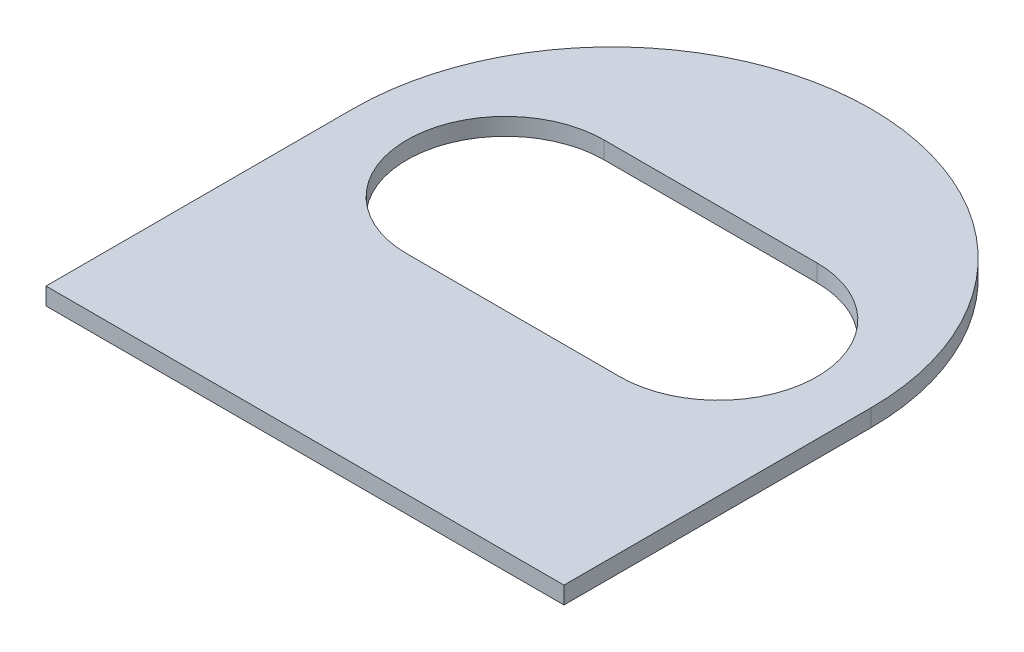
SolidWorks part; units mm, degrees
ref_plane "Front Plane" through (0, 0, 0) normal (0, 0, 1) x (1, 0, 0)
ref_plane "Top Plane" through (0, 0, 0) normal (0, 1, 0) x (1, 0, 0)
ref_plane "Right Plane" through (0, 0, 0) normal (1, 0, 0) x (0, 0, -1)
sketch "Sketch1" plane through (0, 0, 0) normal (0, 1, 0) x (1, 0, 0)
  line L0 (12.3363, 0) -> (-12.3363, 0) construction
  line L6 (-30, 0) -> (-30, -35.56)
  line L7 (-30, -35.56) -> (30, -35.56)
  line L8 (30, 0) -> (30, -35.56)
  line L9 (12.3363, -11.419) -> (-12.3363, -11.419)
  line L10 (12.3363, 11.419) -> (-12.3363, 11.419)
  arc A0 (30, 0) -> (-30, 0) centre (0, 0) ccw
  arc A1 (12.3363, -11.419) -> (12.3363, 11.419) centre (12.3363, 0) ccw
  arc A2 (-12.3363, 11.419) -> (-12.3363, -11.419) centre (-12.3363, 0) ccw
  point P6 (0, -35.56)
  point P9 (0, 0)
  dimension "D1" = 60
  dimension "D2" = 35.56
extrude "Boss-Extrude1" add sketch "Sketch1" along normal blind 2
